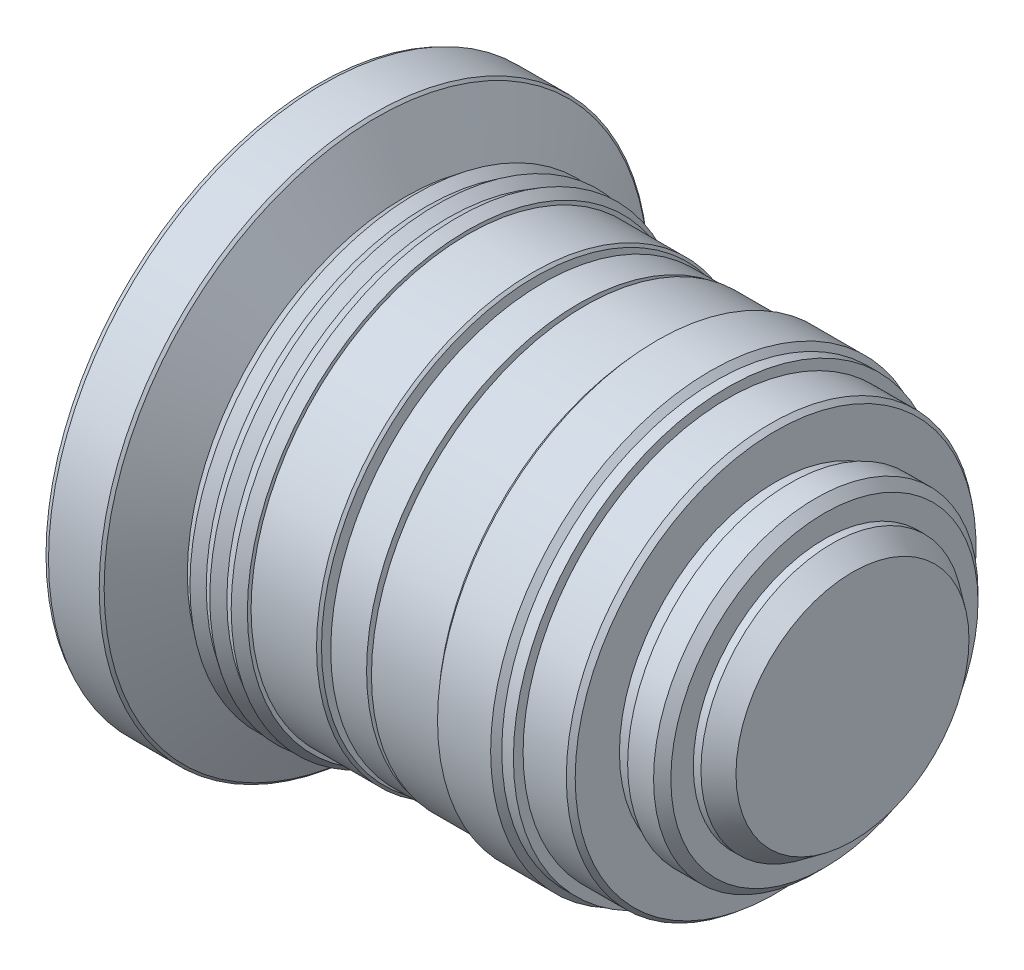
SolidWorks part; units mm, degrees
ref_plane "Спереди" through (0, 0, 0) normal (0, 0, 1) x (1, 0, 0)
ref_plane "Сверху" through (0, 0, 0) normal (0, 1, 0) x (1, 0, 0)
ref_plane "Справа" through (0, 0, 0) normal (1, 0, 0) x (0, 0, -1)
sketch "Model" plane through (0, 0, 0) normal (0, 0, 1) x (1, 0, 0)
  line L0 (0, 0) -> (0, -22.2974)
  line L1 (0, -22.2974) -> (0.407, -22.5)
  line L2 (0.407, -22.5) -> (4.5632, -22.5)
  line L3 (4.5632, -22.5) -> (4.7656, -22.2974)
  line L4 (4.7656, -22.2974) -> (7.1326, -17.8471)
  line L5 (7.1326, -17.8471) -> (8.0341, -18.5333)
  line L6 (8.0341, -18.5333) -> (8.8795, -18.0455)
  line L7 (8.8795, -18.0455) -> (9.7248, -18.6011)
  line L8 (9.7248, -18.6011) -> (10.57, -18.0455)
  line L9 (10.57, -18.0455) -> (11.4103, -18.5306)
  line L10 (11.4103, -18.5306) -> (12.2507, -18.0455)
  line L11 (12.2507, -18.0455) -> (12.2507, -17.7417)
  line L12 (12.2507, -17.7417) -> (17.6163, -17.7417)
  line L13 (17.6163, -17.7417) -> (17.8189, -17.5391)
  line L14 (17.8189, -17.5391) -> (17.8189, -16.4256)
  line L15 (17.8189, -16.4256) -> (18.426, -16.4256)
  line L16 (18.426, -16.4256) -> (18.426, -17.3871)
  line L17 (18.426, -17.3871) -> (21.3621, -17.3871)
  line L18 (21.3621, -17.3871) -> (21.3621, -16.4256)
  line L19 (21.3621, -16.4256) -> (21.8682, -16.4256)
  line L20 (21.8682, -16.4256) -> (21.8682, -17.4939)
  line L21 (21.8682, -17.4939) -> (27.3349, -17.4939)
  line L22 (27.3349, -17.4939) -> (27.7907, -18)
  line L23 (27.7907, -18) -> (32.1439, -18)
  line L24 (32.1439, -18) -> (32.5993, -17.5445)
  line L25 (32.5993, -17.5445) -> (33.5524, -17.5445)
  line L26 (33.5524, -17.5445) -> (33.5523, -16.75)
  line L27 (33.5523, -16.75) -> (37.0951, -16.75)
  line L28 (37.0951, -16.75) -> (37.5, -16.4256)
  line L29 (37.5, -16.4256) -> (37.5, -12.8017)
  line L30 (37.5, -12.8017) -> (38.6654, -12.8017)
  line L31 (38.6654, -12.8017) -> (38.6654, -13.2943)
  line L32 (38.6654, -13.2943) -> (40.7913, -13.2943)
  line L33 (40.7913, -13.2943) -> (41.5, -12.5867)
  line L34 (41.5, -12.5867) -> (41.5, -10.75)
  line L35 (41.5, -10.75) -> (42.1294, -10.75)
  line L36 (42.1294, -10.75) -> (43.8, -9.5485)
  line L37 (43.8, -9.5485) -> (43.8, 0)
  line L38 (0, 0) -> (43.8, 0)
  dimension "D1" = 37.5
  dimension "D2" = 4
  dimension "D3" = 2.3
  dimension "D4" = 22.5
  dimension "D5" = 16.75
  dimension "D6" = 10.75
  dimension "D7" = 18
revolve "Повернуть1" add sketch "Model" angle 360 about L38
